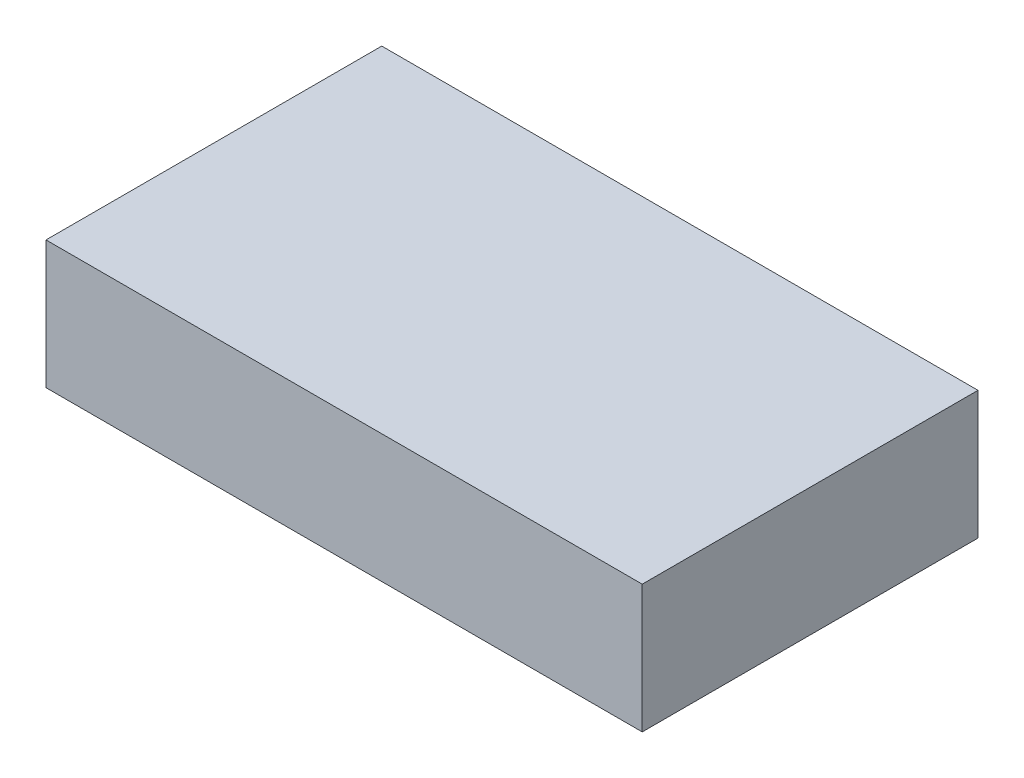
SolidWorks part; units mm, degrees
ref_plane "Front Plane" through (0, 0, 0) normal (0, 0, 1) x (1, 0, 0)
ref_plane "Top Plane" through (0, 0, 0) normal (0, 1, 0) x (1, 0, 0)
ref_plane "Right Plane" through (0, 0, 0) normal (1, 0, 0) x (0, 0, -1)
sketch "Sketch1" plane through (0, 0, 0) normal (0, 0, 1) x (1, 0, 0)
  line L1 (-27.2077, 6.5198) -> (8.3089, 6.5198)
  line L2 (-27.2077, 6.5198) -> (-27.2077, 14.1433)
  line L3 (-27.2077, 14.1433) -> (8.3089, 14.1433)
  line L4 (8.3089, 6.5198) -> (8.3089, 14.1433)
  line L5 (-27.2077, 6.5198) -> (8.3089, 14.1433) construction
  line L6 (-27.2077, 14.1433) -> (8.3089, 6.5198) construction
  point P4 (-9.4494, 10.3316)
extrude "Boss-Extrude1" add sketch "Sketch1" along normal blind 20
